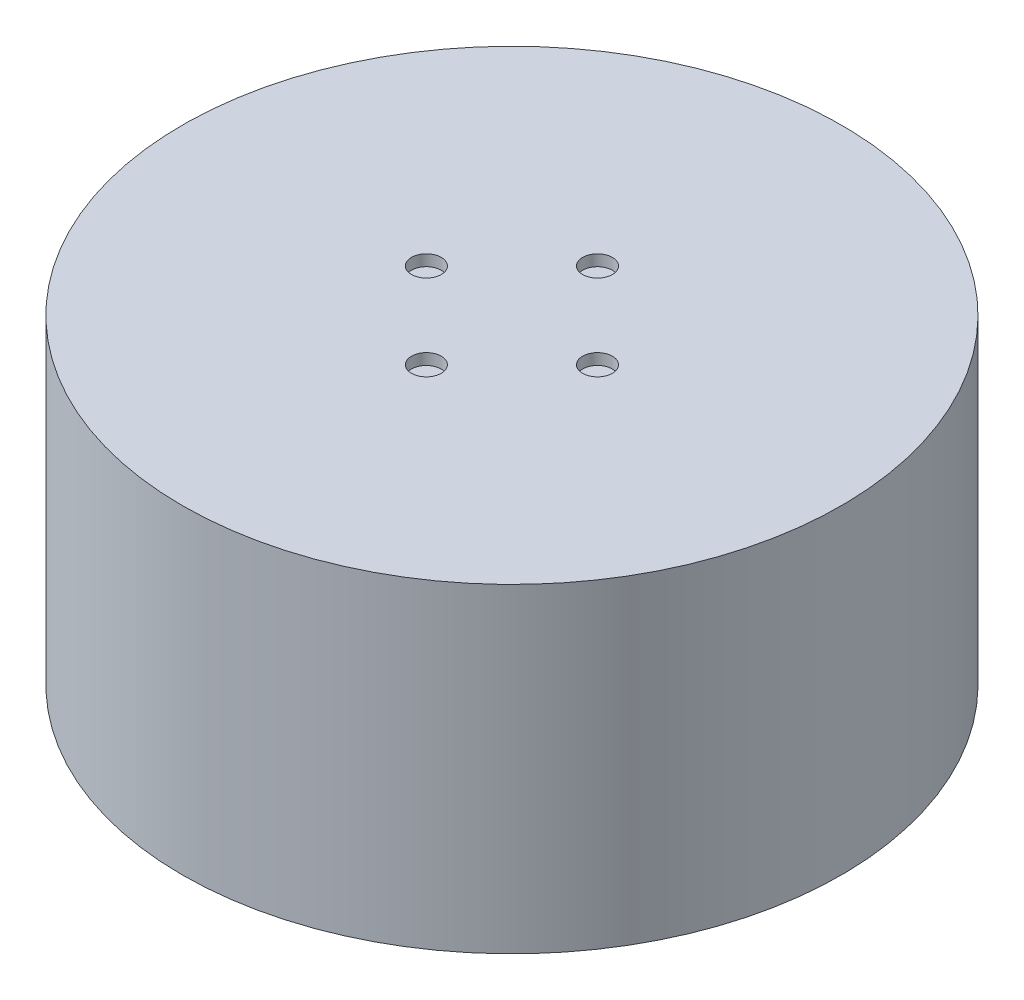
SolidWorks part; units mm, degrees
ref_plane "Front Plane" through (0, 0, 0) normal (0, 0, 1) x (1, 0, 0)
ref_plane "Top Plane" through (0, 0, 0) normal (0, 1, 0) x (1, 0, 0)
ref_plane "Right Plane" through (0, 0, 0) normal (1, 0, 0) x (0, 0, -1)
sketch "Sketch1" plane through (0, 0, 0) normal (0, 1, 0) x (1, 0, 0)
  circle A0 centre (0, 0) radius 44.3
  dimension "D1" = 88.6
extrude "Boss-Extrude1" add sketch "Sketch1" along normal blind 43
sketch "Sketch2" plane through (0, 0, 0) normal (0, -1, 0) x (1, 0, 0)
  circle A0 centre (0, 0) radius 16 construction
  circle A1 centre (0, 16) radius 2
  circle A2 centre (16, 0) radius 2
  circle A3 centre (0, -16) radius 2
  circle A4 centre (-16, 0) radius 2
  point P14 (0, 0)
  dimension "D1" = 32
  dimension "D2" = 4
  dimension "D3" = 4
extrude "Cut-Extrude1" cut sketch "Sketch2" against normal blind 1.5
sketch "Sketch3" plane through (0, 0, 0) normal (0, -1, 0) x (1, 0, 0)
  line L0 (0, 0) -> (0, 16) construction
  line L1 (0, 16) -> (16, 0) construction
  line L2 (16, 0) -> (0, 0) construction
  line L3 (0, 0) -> (21.2132, 21.2132) construction
  line L4 (17.6777, 24.7487) -> (24.7487, 17.6777) construction
  line L5 (20.5061, 27.5772) -> (27.5772, 20.5061) construction
  line L6 (14.8492, 21.9203) -> (21.9203, 14.8492) construction
  line L7 (19.799, 26.8701) -> (26.8701, 19.799)
  line L8 (15.5563, 22.6274) -> (22.6274, 15.5563)
  arc A0 (20.5061, 27.5772) -> (14.8492, 21.9203) centre (17.6777, 24.7487) ccw construction
  arc A1 (21.9203, 14.8492) -> (27.5772, 20.5061) centre (24.7487, 17.6777) ccw construction
  arc A2 (22.6274, 15.5563) -> (26.8701, 19.799) centre (24.7487, 17.6777) ccw
  arc A3 (19.799, 26.8701) -> (15.5563, 22.6274) centre (17.6777, 24.7487) ccw
  point P9 (21.2132, 21.2132)
  dimension "D3" = 4
  dimension "D1" = 30
  dimension "D2" = 10
  dimension "D4" = 1
extrude "Boss-Extrude2" add sketch "Sketch3" along normal blind 6
sketch "Sketch4" plane through (0, 43, 0) normal (0, 1, 0) x (1, 0, 0)
  circle A0 centre (0, 0) radius 11.5 construction
  circle A1 centre (0, 11.5) radius 2
  circle A2 centre (11.5, 0) radius 2
  circle A3 centre (0, -11.5) radius 2
  circle A4 centre (-11.5, 0) radius 2
  point P14 (0, 0)
  dimension "D2" = 4
  dimension "D3" = 4
  dimension "D1" = 23
extrude "Cut-Extrude2" cut sketch "Sketch4" against normal blind 1.5
equation "\"Np\"= 40"
equation "\"module\"= 0.8"
equation "\"pressure angle\"= 20deg"
equation "\"h_a\"= 1 * \"module\"'addendum"
equation "\"h_b\"= 1.25 * \"module\"'dedendum"
equation "\"clr_tip_root\"= \"h_f\" - \"h_a\"'clearance of gear tooth tip and root"
equation "\"dp_p\"= \"module\" * \"Np\"'PCD"
equation "\"db_p\"= \"dp_p\" * cos ( \"pressure angle\" )'base CD"
equation "\"fw_p\"= \"fw_r\""
equation "\"alpha_p\"= sqr ( \"dp_p\" ^ 2 - \"db_p\" ^ 2 ) / \"db_p\" * 180 / pi - \"pressure angle\""
equation "\"beta_p\"= ( 360 / ( 4 * \"Np\" ) - \"alpha_p\" ) * 2"
equation "\"Nr\"= \"Ns\" + 2 * \"Np\"'num teeth"
equation "\"pressure_angle\"= 20deg"
equation "\"h_f\"= 1.25 * \"module\"'dedendum"
equation "\"dp_r\"= \"module\" * \"Nr\"'PCD"
equation "\"db_r\"= \"dp_r\" * cos ( \"pressure_angle\" )'base CD"
equation "\"fw_r\"= 11.5mm'face width"
equation "\"alpha_r\"= sqr ( \"dp_r\" ^ 2 - \"db_r\" ^ 2 ) / \"db_r\" * 180 / pi - \"pressure_angle\""
equation "\"beta_r\"= ( 360 / ( 4 * \"Nr\" ) + \"alpha_r\" ) * 2"
equation "\"bearing_ID\"= \"module\" * ( \"Ns\" + \"Np\" ) + 10"
equation "\"bearing_OD\"= 1.18 * \"bearing_ID\" + 8.57"
equation "\"bearing_height\"= 0.09 * \"bearing_ID\" + 4.62"
equation "\"clearance_planet\"=1.5"
equation "\"case_dist\"= \"sec_carrier_thickness\" + \"clearance_planet\" + \"sun_coupler_hub_thickness\" - \"case_mounting_surface_height\""
equation "\"Motor_case_OD_max\"= \"case_mounting_PCD\" + \"case_mounting_hole_allen_socket_dia\" + \"clearance_case_mount_holes_shell_thickness\" * 2"
equation "\"case_mounting_PCD\"= \"motor_case_OD_base\" + \"case_mounting_hole_shift\" * 2"
equation "\"bearing mount thickness\"= IIF((\"bearing_OD\" + \"output_mounting_hole_dia\" * 4) > (\"Nr\" * \"module\" + 2 * \"h_b\"), \"output_mounting_hole_dia\" * 2, ((\"Nr\" * \"module\" + 2 * \"h_b\" - (\"bearing_OD\" + \"output_mounting_hole_dia\" * 4)) / 2) + \"output_mounting_hole_dia\" * 2 + \"standard_clearance_1_5mm\")"
equation "\"case_mounting_hole_dia\"=3"
equation "\"output_mounting_PCD\"= \"bearing_OD\" + \"bearing mount thickness\""
equation "\"output_mounting_hole_dia\"= 4"
equation "\"clearance_case_mount_holes_shell_thickness\"= 1"
equation "\"motor_case_OD_base\"= \"motor_OD\" + \"clearance_motor_and_case\" * 2 + \"Motor_case_thickness\" * 2"
equation "\"sec_carrier_thickness\"= 5"
equation "\"sun_coupler_hub_thickness\"= 4"
equation "\"clearance_sun_coupler_sec_carrier\"= 1.5"
equation "\"clearance_motor_and_case\" = IIF(\"ring_OD\" < \"motor_OD\", 5, (\"ring_OD\" - \"motor_OD\")/2 + 5)"
equation "\"motor_OD\"= 88.6"
equation "\"Motor_case_thickness\"= 2.5"
equation "\"Motor_case_ID\"= \"motor_OD\" + \"clearance_motor_and_case\" * 2"
equation "\"case_mounting_hole_shift\"= \"case_mounting_hole_dia\" / 2 - 0.5"
equation "\"output_mounting_nut_wrench_size\"= 7"
equation "\"output_mounting_nut_thickness\"= 3.2"
equation "\"case_mounting_hole_allen_socket_dia\"= 5.5"
equation "\"output_mounting_nut_depth\"= 3"
equation "\"case_mounting_bolt_depth\"= 4.5"
equation "\"Ns\"= 20"
equation "\"ring_radial_thickness\"= 5"
equation "\"ring_OD\"= \"Nr\" * \"module\" + \"ring_radial_thickness\" * 2"
equation "\"ring_to_chamfer_clearance\"= 2"
equation "\"Motor_case_OD_base_to_chamfer\"=5"
equation "\"pattern_offset_from_motor_case_OD_base\"= 3"
equation "\"pattern_bulge_dia\"= 3"
equation "\"pattern_num_bulge\"= 18"
equation "\"pattern_depth\"= 2"
equation "\"motor_height\"= 43"
equation "\"case_mounting_wrench_size\"= 5.5"
equation "\"case_mounting_nut_clearance\"= 2"
equation "\"base_plate_thickness\"= 4"
equation "\"case_mounting_nut_thickness\"= 2.4"
equation "\"case_mounting_surface_height\"= 4"
equation "\"motor_mount_hole_PCD\"= 32"
equation "\"motor_mount_hole_dia\"= 4"
equation "\"motor_mount_hole_num\"= 4"
equation "\"central_hole_offset_from_motor_mount_PCD\"= 5"
equation "\"wire_slot_dist_from_center\"= 30"
equation "\"wire_slot_length\"= 10"
equation "\"wire_slot_radius\"= 4"
equation "\"driver_upper_holes_dist_from_center\"= 23"
equation "\"driver_lower_holes_dist_from_center\"= 15"
equation "\"driver_side_holes_dist_from_center\"= 20"
equation "\"driver_mount_holes_dia\"= 2.5"
equation "\"driver_mount_inserts_OD\"= 3.5"
equation "\"driver_mount_thickness\"= 1.5"
equation "\"driver_mount_height\"= 4"
equation "\"air_flow_hole_offset\"= 3"
equation "\"num_planet\"= 3"
equation "\"planet_pin_bolt_dia\"= 5"
equation "\"planet_pin_socket_head_dia\"= 8.5"
equation "\"carrier_PCD\"= ( \"Np\" + \"Ns\" ) * \"module\""
equation "\"planet_shaft_dia\"= 8"
equation "\"planet_shaft_step_offset\"= 1"
equation "\"carrier_trapezoidal_support_sun_offset\"= 5"
equation "\"carrier_trapezoidal_support_hole_PCD_offset_bearing_ID\"= 4"
equation "\"carrier_trapezoidal_support_hole_dia\"= 3"
equation "\"carrier_trapezoidal_support_hole_socket_head_dia\"= 5.5"
equation "\"carrier_bearing_step_width\"= 1.5"
equation "\"standard_clearance_1_5mm\"=1.5"
equation "\"standard_fillet_1_5mm\"= 1.5"
equation "\"sun_shaft_bearing_OD\"= 16"
equation "\"sun_shaft_bearing_width\"= 4"
equation "\"standard_bearing_insertion_chamfer\"= 0.5"
equation "\"carrier_trapezoidal_support_hole_wrench_size\"= 5.5"
equation "\"planet_pin_bolt_wrench_size\"= 8"
equation "\"planet_bearing_OD\"= 12"
equation "\"planet_bearing_width\"= 3"
equation "\"planet_bore\"= 10"
equation "\"D1@Boss-Extrude1\"=\"motor_height\""
equation "\"D1@Sketch1\"=\"motor_OD\""
equation "\"D1@Sketch2\"=\"motor_mount_hole_PCD\""
equation "\"D2@Sketch2\"=\"motor_mount_hole_dia\""
equation "\"D3@Sketch2\"=\"motor_mount_hole_num\""
equation "\"D1@Cut-Extrude1\"=\"standard_clearance_1_5mm\""
equation "\"D1@Sketch3\"=\"wire_slot_dist_from_center\""
equation "\"D2@Sketch3\"=\"wire_slot_length\""
equation "\"D3@Sketch3\"=\"wire_slot_radius\""
equation "\"D1@Boss-Extrude2\"=\"standard_clearance_1_5mm\"*4"
equation "\"motor_output_hole_PCD\"= 23"
equation "\"motor_output_hole_dia\"= 4"
equation "\"motor_output_hole_num\"= 4"
equation "\"D1@Sketch4\"=\"motor_output_hole_PCD\""
equation "\"D2@Sketch4\"=\"motor_output_hole_dia\""
equation "\"D3@Sketch4\"=\"motor_output_hole_num\""
equation "\"D1@Cut-Extrude2\"=\"standard_clearance_1_5mm\""
equation "\"dp_s\"= \"module\" * \"Ns\"'PCD"
equation "\"db_s\"= \"dp_s\" * cos ( \"pressure angle\" )'base CD"
equation "\"fw_s_calc\"= 13mm'face width"
equation "\"alpha_s\"= sqr ( \"dp_s\" ^ 2 - \"db_s\" ^ 2 ) / \"db_s\" * 180 / pi - \"pressure angle\""
equation "\"beta_s\"= ( 360 / ( 4 * \"Ns\" ) - \"alpha_s\" ) * 2"
equation "\"sun_shaft_bearing_ID\"= 8"
equation "\"sun_hub_dia\"= \"motor_output_hole_PCD\" + \"motor_output_hole_dia\" + \"standard_clearance_1_5mm\" * 4"
equation "\"sun_central_bolt_dia\"= 5"
equation "\"sun_central_bolt_socket_head_dia\"= 8.5"
equation "\"fw_s_used\"= \"fw_p\" + \"clearance_planet\" + \"sec_carrier_thickness\" + \"standard_clearance_1_5mm\""
equation "\"motor_output_hole_CSK_OD\"= 9'8.96 is exact value"
equation "\"motor_output_hole_CSK_head_height\"= 2.5"
equation "\"bearing_retainer_thickness\"= 2"
